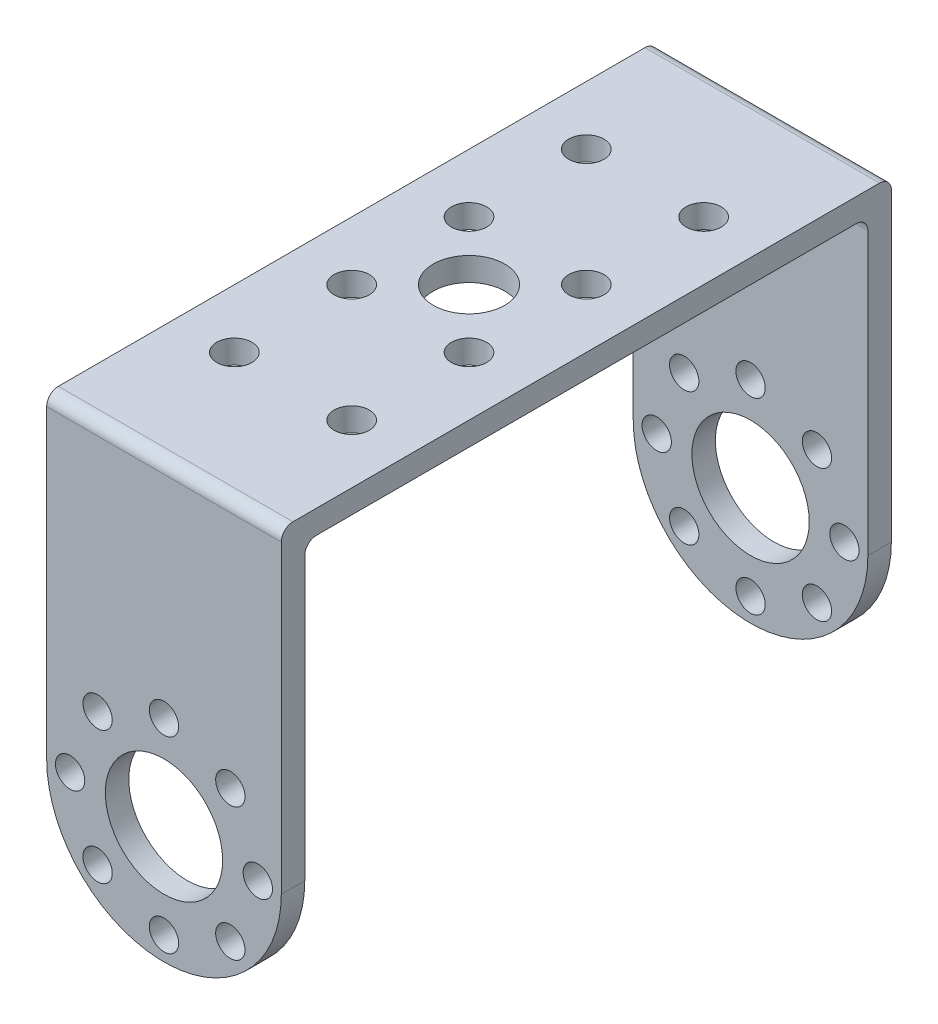
SolidWorks part; units mm, degrees
ref_plane "前视基准面" through (0, 0, 0) normal (0, 0, 1) x (1, 0, 0)
ref_plane "上视基准面" through (0, 0, 0) normal (0, 1, 0) x (1, 0, 0)
ref_plane "右视基准面" through (0, 0, 0) normal (1, 0, 0) x (0, 0, -1)
sketch "草图1" plane through (0, 0, 0) normal (1, 0, 0) x (0, 0, -1)
  line L0 (-24, -18.5) -> (-24, 16.5)
  line L1 (-26, -18.5) -> (-24, -18.5)
  line L2 (-26, -18.5) -> (-26, 18.5)
  line L3 (-26, 18.5) -> (26, 18.5)
  line L4 (26, -18.5) -> (26, 18.5)
  line L5 (-26, -18.5) -> (26, 18.5) construction
  line L6 (-26, 18.5) -> (26, -18.5) construction
  line L7 (-24, 16.5) -> (24, 16.5)
  line L8 (24, 16.5) -> (24, -18.5)
  line L9 (24, -18.5) -> (26, -18.5)
  point P0 (0, 0)
  dimension "D1" = 52
  dimension "D2" = 37
  dimension "D3" = 2
  dimension "D4" = 2
  dimension "D5" = 2
extrude "凸台-拉伸1" add sketch "草图1" along normal blind 20
fillet "圆角1" radius 1 4 edges at (10, 16.5, -24) (10, 16.5, 24) (10, 18.5, -26) (10, 18.5, 26)
sketch "草图2" plane through (0, 0, 26) normal (0, 0, 1) x (1, 0, 0)
  line L2 (0, -8.5) -> (0, -18.5)
  line L3 (0, -18.5) -> (20, -18.5)
  line L4 (20, -18.5) -> (20, -8.5)
  arc A0 (0, -8.5) -> (20, -8.5) centre (10, -8.5) ccw
  line M2 (20, -18.5) -> (20, 17.5)
  line M4 (0, 17.5) -> (0, -18.5)
  line M5 (0, -18.5) -> (20, -18.5)
extrude "切除-拉伸1" cut sketch "草图2" against normal blind 50000 contours A0 M4 M5 | A0 L3 M2
sketch "草图3" plane through (0, 0, 26) normal (0, 0, 1) x (1, 0, 0)
  circle A0 centre (10, -8.5) radius 5
  dimension "D1" = 10
extrude "切除-拉伸2" cut sketch "草图3" against normal blind 500
sketch "草图4" plane through (0, 0, 26) normal (0, 0, 1) x (1, 0, 0)
  line L0 (-2.3741, -8.5) -> (25.5776, -8.5) construction
  circle A0 centre (18, -8.5) radius 1.25
  circle A1 centre (10, -8.5) radius 5 construction
  dimension "D1" = 2.5
  dimension "D2" = 8
extrude "切除-拉伸3" cut sketch "草图4" against normal blind 5000
pattern_circular "阵列(圆周)1" count 8 over 360 about axis through (10, -8.5, 0) along (0, 0, 1) of "切除-拉伸3"
sketch "草图5" plane through (0, 18.5, 0) normal (0, 1, 0) x (1, 0, 0)
  line L0 (-9.8163, 0) -> (34.6252, 0) construction
  line L1 (10, 33.3615) -> (10, -35.0916) construction
  line L2 (-3.2827, 5) -> (39.003, 5) construction
  line L3 (-3.9792, 15) -> (33.3318, 15) construction
  circle A0 centre (10, 0) radius 3.05
  circle A1 centre (15, 15) radius 1.5
  circle A2 centre (5, 15) radius 1.5
  circle A3 centre (5, 5) radius 1.5
  circle A4 centre (15, 5) radius 1.5
  circle A5 centre (15, -5) radius 1.5
  circle A6 centre (5, -5) radius 1.5
  circle A7 centre (5, -15) radius 1.5
  circle A8 centre (15, -15) radius 1.5
  dimension "D1" = 6.1
  dimension "D4" = 3
  dimension "D5" = 5
  dimension "D2" = 5
  dimension "D3" = 10
  dimension "D6" = 5
  dimension "D7" = 5
  dimension "D8" = 5
extrude "切除-拉伸4" cut sketch "草图5" against normal blind 5000
